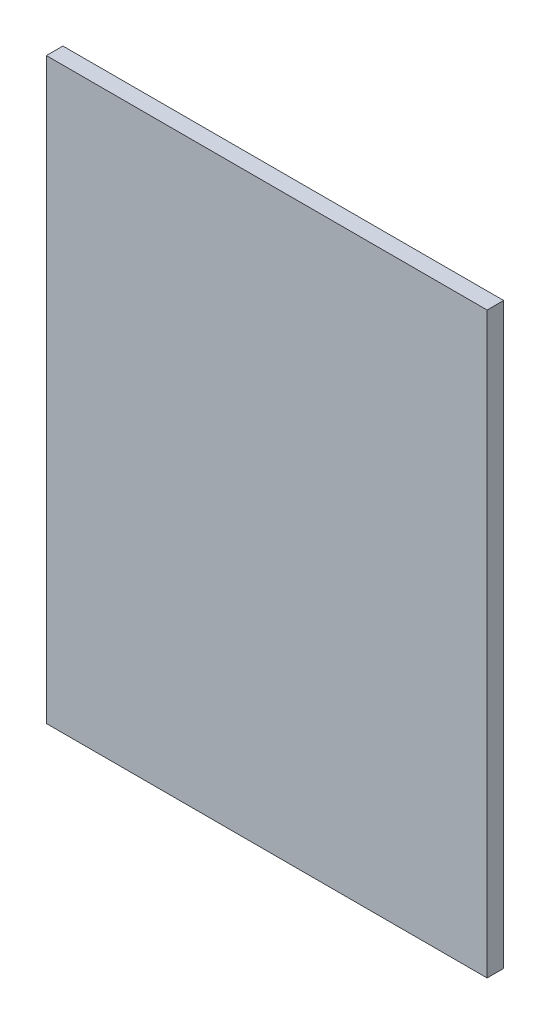
SolidWorks part; units mm, degrees
ref_plane "정면" through (0, 0, 0) normal (0, 0, 1) x (1, 0, 0)
ref_plane "윗면" through (0, 0, 0) normal (0, 1, 0) x (1, 0, 0)
ref_plane "우측면" through (0, 0, 0) normal (1, 0, 0) x (0, 0, -1)
sketch "스케치1" plane through (0, 0, 0) normal (0, 0, 1) x (1, 0, 0)
  line L1 (-40, -52.5) -> (40, -52.5)
  line L2 (-40, -52.5) -> (-40, 52.5)
  line L3 (-40, 52.5) -> (40, 52.5)
  line L4 (40, -52.5) -> (40, 52.5)
  line L5 (-40, -52.5) -> (40, 52.5) construction
  line L6 (-40, 52.5) -> (40, -52.5) construction
  point P0 (0, 0)
  dimension "D1" = 80
  dimension "D2" = 105
extrude "보스-돌출1" add sketch "스케치1" along normal blind 3
